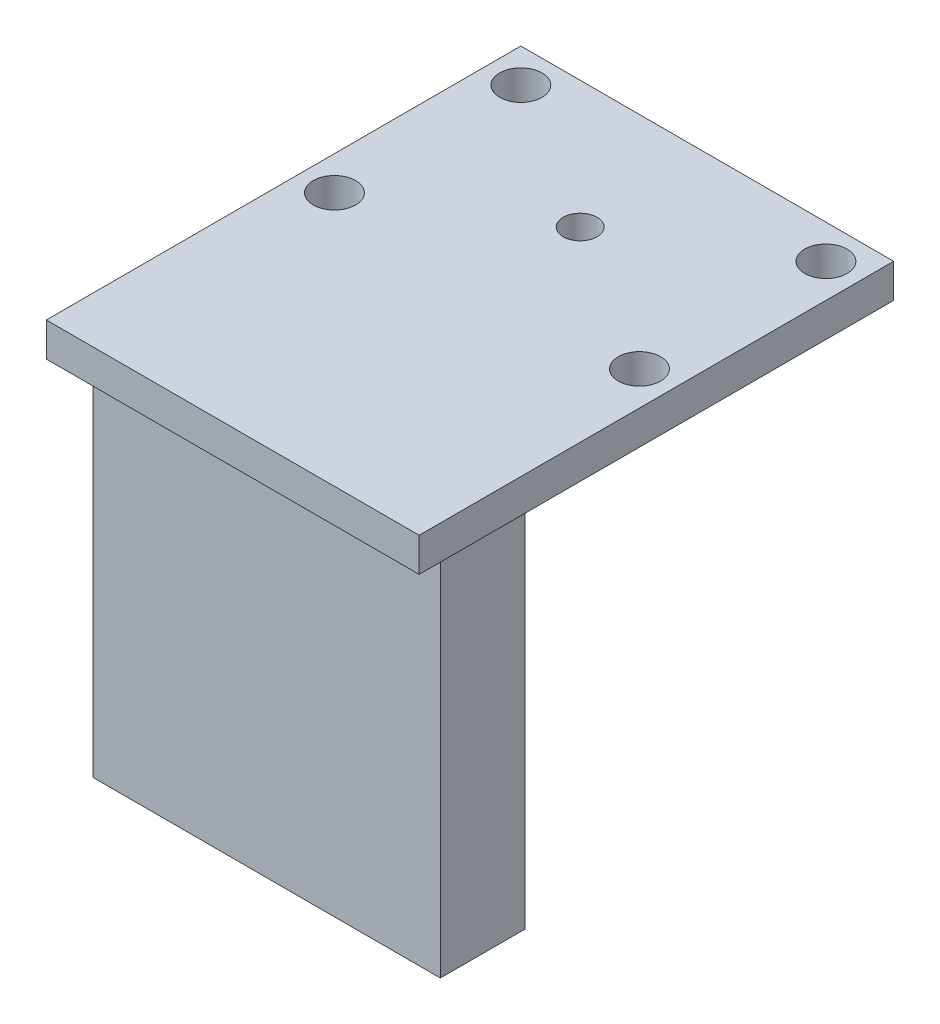
SolidWorks part; units mm, degrees
ref_plane "前视基准面" through (0, 0, 0) normal (0, 0, 1) x (1, 0, 0)
ref_plane "上视基准面" through (0, 0, 0) normal (0, 1, 0) x (1, 0, 0)
ref_plane "右视基准面" through (0, 0, 0) normal (1, 0, 0) x (0, 0, -1)
sketch "草图1" plane through (0, 0, 0) normal (0, 1, 0) x (1, 0, 0)
  line L1 (-11, -14) -> (11, -14)
  line L2 (-11, -14) -> (-11, 14)
  line L3 (-11, 14) -> (11, 14)
  line L4 (11, -14) -> (11, 14)
  line L5 (-11, -14) -> (11, 14) construction
  line L6 (-11, 14) -> (11, -14) construction
  point P0 (0, 0)
  dimension "D1" = 22
  dimension "D2" = 28
extrude "凸台-拉伸1" add sketch "草图1" along normal blind 2
sketch "草图2" plane through (0, 2, 0) normal (0, 1, 0) x (1, 0, 0)
  line L0 (0, 14) -> (0, -10.1937) construction
  line L1 (11, 14) -> (-11, 14) construction
  line L2 (-9, 12) -> (-9, 1) construction
  circle A0 centre (9, 12) radius 1.25
  circle A1 centre (-9, 12) radius 1.25
  circle A2 centre (-9, 1) radius 1.25
  circle A3 centre (9, 1) radius 1.25
  dimension "D1" = 18
  dimension "D2" = 2.5
  dimension "D5" = 2
  dimension "D4" = 11
  dimension "D3" = 2
extrude "切除-拉伸1" cut sketch "草图2" against normal up to next
sketch "草图3" plane through (0, 0, 0) normal (0, -1, 0) x (1, 0, 0)
  line L0 (0, 12.4135) -> (0, -8.5729) construction
  line L2 (-10.25, 7) -> (10.25, 7)
  line L3 (-10.25, 7) -> (-10.25, 12)
  line L4 (-10.25, 12) -> (10.25, 12)
  line L5 (10.25, 7) -> (10.25, 12)
  line L6 (-10.25, 7) -> (10.25, 12) construction
  line L7 (-10.25, 12) -> (10.25, 7) construction
  line L8 (-11, 14) -> (11, 14) construction
  point P3 (0, 9.5)
  dimension "D1" = 5
  dimension "D2" = 20.5
  dimension "D3" = 7
extrude "凸台-拉伸2" add sketch "草图3" along normal blind 22
sketch "草图4" plane through (0, 2, 0) normal (0, 1, 0) x (1, 0, 0)
  line L0 (-9, 12) -> (9, 1) construction
  line L1 (-9, 1) -> (9, 12) construction
  circle A0 centre (0, 6.5) radius 1
  dimension "D1" = 2
extrude "切除-拉伸2" cut sketch "草图4" against normal up to next and the other way through all
